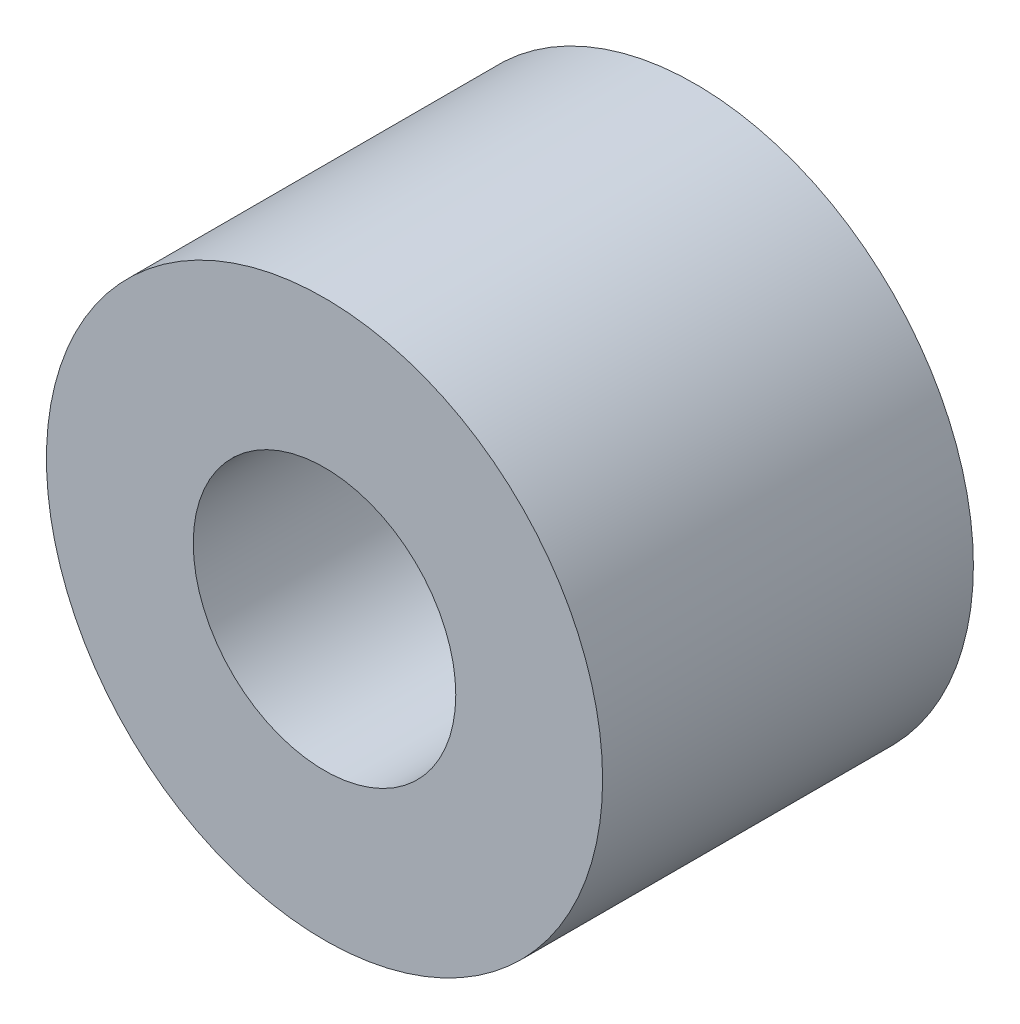
SolidWorks part; units mm, degrees
material "Birch Plywood"
ref_plane "Front Plane" through (0, 0, 0) normal (0, 0, 1) x (1, 0, 0)
ref_plane "Top Plane" through (0, 0, 0) normal (0, 1, 0) x (1, 0, 0)
ref_plane "Right Plane" through (0, 0, 0) normal (1, 0, 0) x (0, 0, -1)
sketch "Sketch1" plane through (0, 0, 0) normal (0, 0, 1) x (1, 0, 0)
  circle A0 centre (0, 0) radius 4.7625
  circle A1 centre (0, 0) radius 2.2479
  dimension "D1" = 4.4958
  dimension "D2" = 9.525
extrude "Boss-Extrude1" add sketch "Sketch1" along normal blind 6.35
